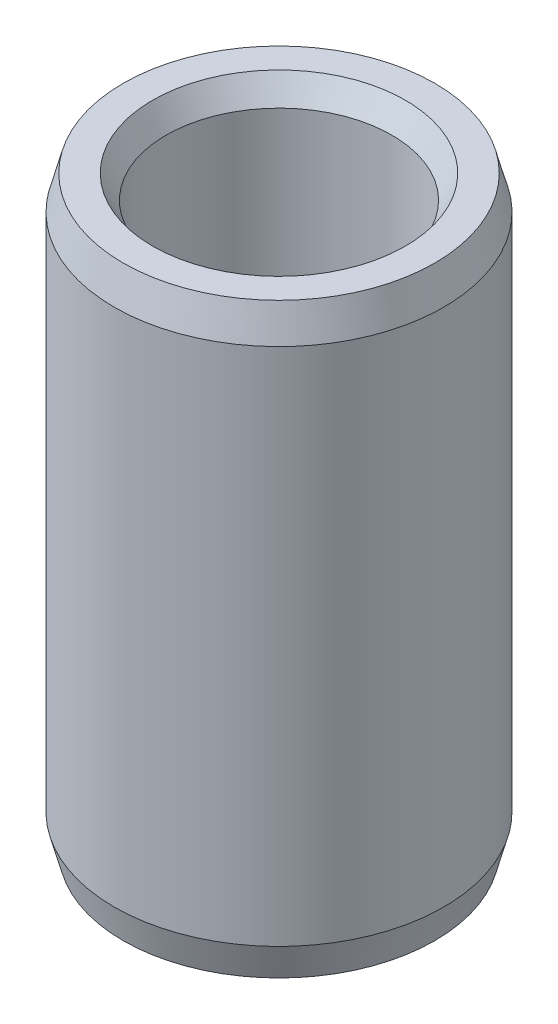
SolidWorks part; units mm, degrees
material "1.7131 (16MnCr5)"
ref_plane "Front Plane" through (0, 0, 0) normal (0, 0, 1) x (1, 0, 0)
ref_plane "Top Plane" through (0, 0, 0) normal (0, 1, 0) x (1, 0, 0)
ref_plane "Right Plane" through (0, 0, 0) normal (1, 0, 0) x (0, 0, -1)
sketch "Sketch1" plane through (0, 0, 0) normal (0, 1, 0) x (1, 0, 0)
  circle A0 centre (0, 0) radius 25
  circle A1 centre (0, 0) radius 36.5
  dimension "D1" = 73
  dimension "D2" = 50
extrude "Boss-Extrude1" add sketch "Sketch1" against normal blind 130
chamfer "Chamfer1" distance 3 angle 60 2 edges at (0, -130, 25) (0, 0, 25)
chamfer "Chamfer2" distance 2 angle 75 1 edges at (0, -130, 36.5)
chamfer "Chamfer3" distance 2 angle 75 1 edges at (0, 0, 36.5)
